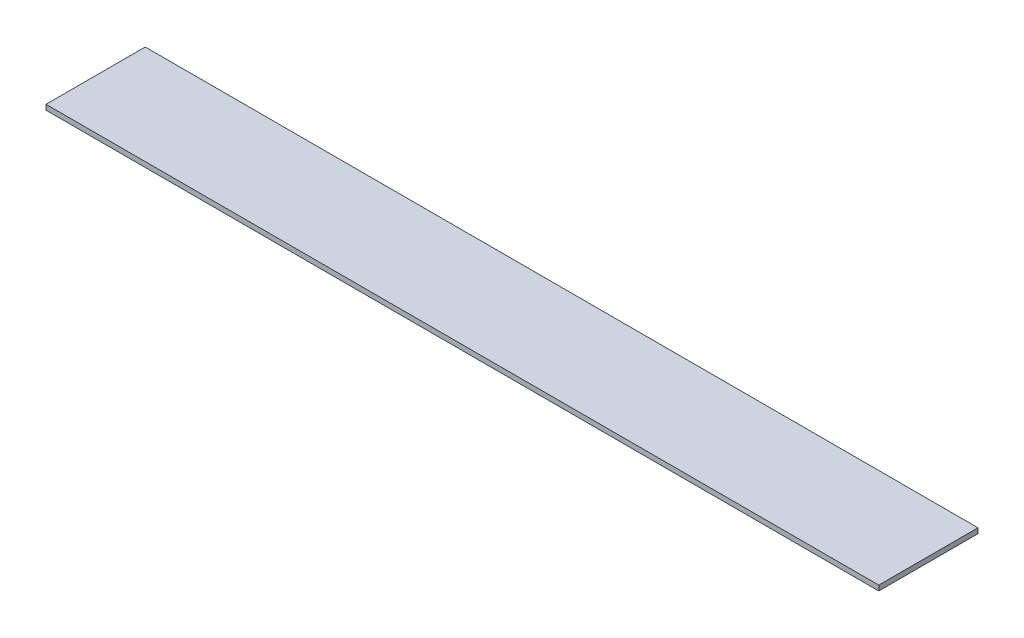
SolidWorks part; units mm, degrees
ref_plane "Ebene vorne" through (0, 0, 0) normal (0, 0, 1) x (1, 0, 0)
ref_plane "Ebene oben" through (0, 0, 0) normal (0, 1, 0) x (1, 0, 0)
ref_plane "Ebene rechts" through (0, 0, 0) normal (1, 0, 0) x (0, 0, -1)
sketch "Skizze1" plane through (0, 0, 0) normal (0, 1, 0) x (1, 0, 0)
  line L1 (0, 0) -> (5035, 0)
  line L2 (0, 0) -> (0, 600)
  line L3 (0, 600) -> (5035, 600)
  line L4 (5035, 0) -> (5035, 600)
  dimension "D1" = 5035
  dimension "D2" = 600
extrude "Aufsatz-Linear austragen1" add sketch "Skizze1" along normal blind 31 contours L2 L1 L4 L3
